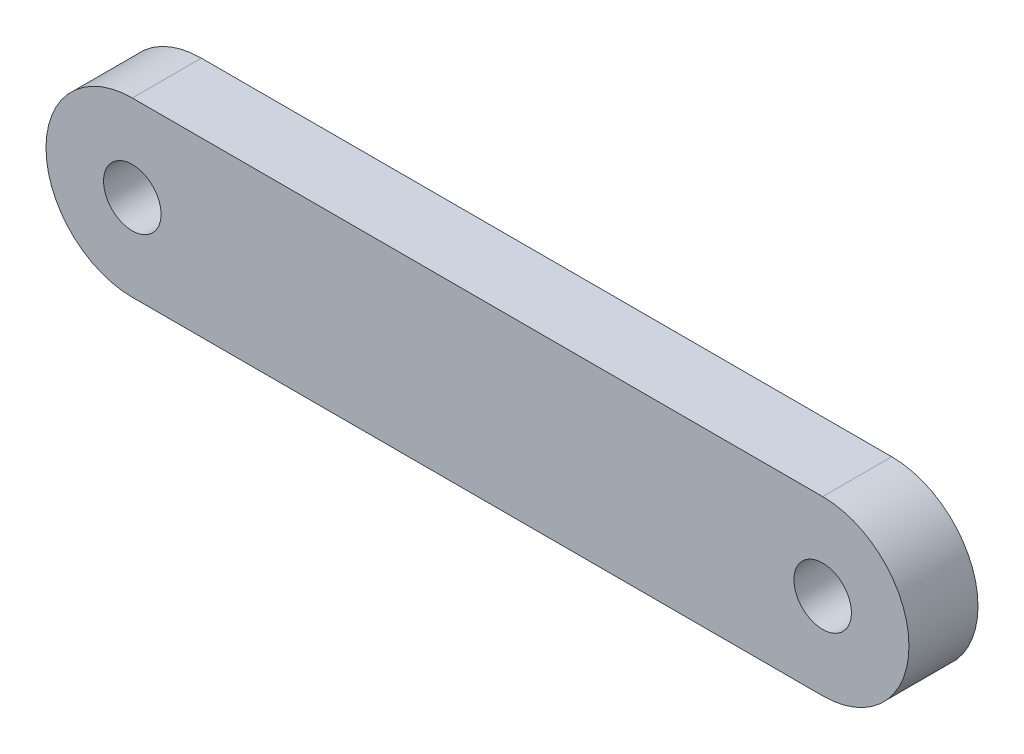
SolidWorks part; units mm, degrees
ref_plane "Front Plane" through (0, 0, 0) normal (0, 0, 1) x (1, 0, 0)
ref_plane "Top Plane" through (0, 0, 0) normal (0, 1, 0) x (1, 0, 0)
ref_plane "Right Plane" through (0, 0, 0) normal (1, 0, 0) x (0, 0, -1)
sketch "Sketch1" plane through (0, 0, 0) normal (0, 0, 1) x (1, 0, 0)
  line L0 (-30, 0) -> (30, 0)
  line L1 (-30, 7.5) -> (30, 7.5)
  line L2 (-30, -7.5) -> (30, -7.5)
  arc A0 (-30, 7.5) -> (-30, -7.5) centre (-30, 0) ccw
  arc A1 (30, -7.5) -> (30, 7.5) centre (30, 0) ccw
  circle A2 centre (-30, 0) radius 2.5
  circle A3 centre (30, 0) radius 2.5
  point P4 (0, 0)
  dimension "D2" = 15
  dimension "D3" = 15
  dimension "D4" = 5
  dimension "D5" = 5
  dimension "D1" = 60
extrude "Boss-Extrude1" add sketch "Sketch1" along normal mid plane 6
